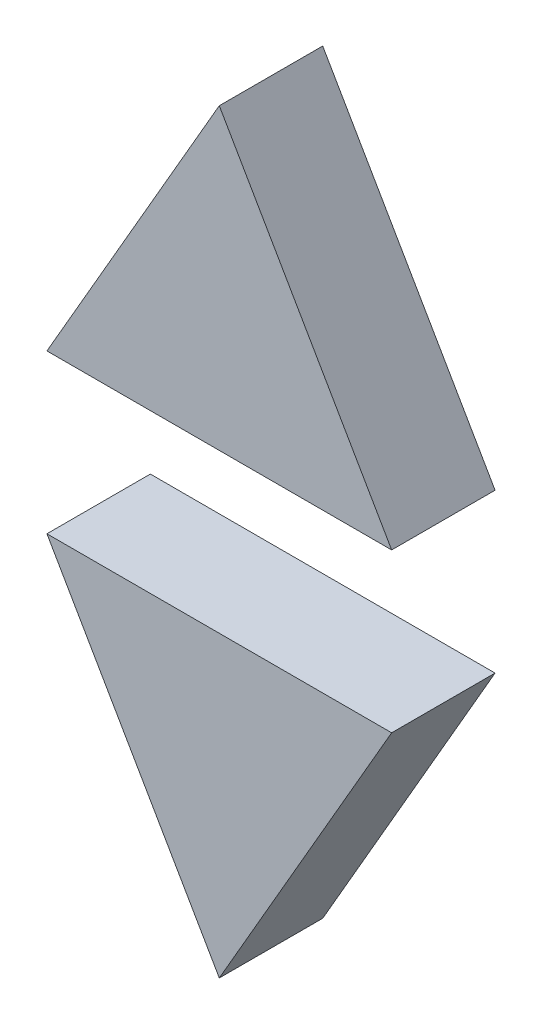
SolidWorks part; units mm, degrees
ref_plane "Front Plane" through (0, 0, 0) normal (0, 0, 1) x (1, 0, 0)
ref_plane "Top Plane" through (0, 0, 0) normal (0, 1, 0) x (1, 0, 0)
ref_plane "Right Plane" through (0, 0, 0) normal (1, 0, 0) x (0, 0, -1)
sketch "Sketch1" plane through (0, 0, 0) normal (0, 0, 1) x (1, 0, 0)
  line L0 (18.1063, 5.1812) -> (23.1063, 13.8414)
  line L1 (23.1063, 13.8414) -> (28.1063, 5.1812)
  line L2 (28.1063, 5.1812) -> (18.1063, 5.1812)
  line L3 (18.1063, 0.5882) -> (28.1063, 0.5882)
  line L4 (28.1063, 0.5882) -> (23.1063, -8.0721)
  line L5 (23.1063, -8.0721) -> (18.1063, 0.5882)
  point P7 (23.1063, 5.1812)
  point P8 (23.1063, 0.5882)
  dimension "D1" = 10
  dimension "D2" = 60
  dimension "D3" = 60
extrude "Boss-Extrude1" add sketch "Sketch1" along normal blind 3
